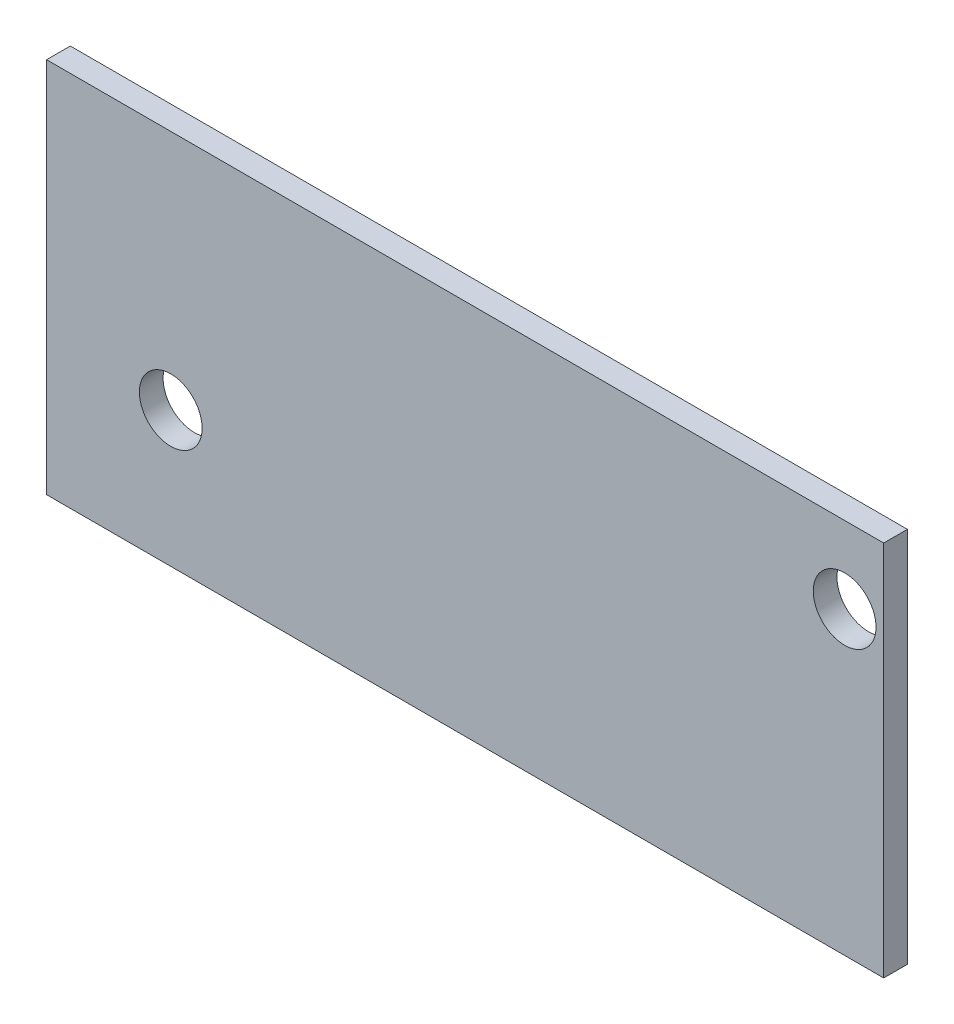
SolidWorks part; units mm, degrees
ref_plane "Front Plane" through (0, 0, 0) normal (0, 0, 1) x (1, 0, 0)
ref_plane "Top Plane" through (0, 0, 0) normal (0, 1, 0) x (1, 0, 0)
ref_plane "Right Plane" through (0, 0, 0) normal (1, 0, 0) x (0, 0, -1)
sketch "Sketch1" plane through (0, 0, 0) normal (0, 0, 1) x (1, 0, 0)
  line L1 (-2.199, 29.7016) -> (57.801, 29.7016)
  line L2 (-2.199, 29.7016) -> (-2.199, 56.7016)
  line L3 (-2.199, 56.7016) -> (57.801, 56.7016)
  line L4 (57.801, 29.7016) -> (57.801, 56.7016)
  dimension "D1" = 60
  dimension "D2" = 27
extrude "Boss-Extrude1" add sketch "Sketch1" along normal blind 1.7
sketch "Sketch2" plane through (0, 0, 0) normal (0, 0, -1) x (-1, 0, 0)
  circle A2 centre (-55.0016, 51.2022) radius 2.25
  circle A3 centre (-6.7016, 39.4022) radius 2.25
extrude "Cut-Extrude1" cut sketch "Sketch2" against normal blind 10
